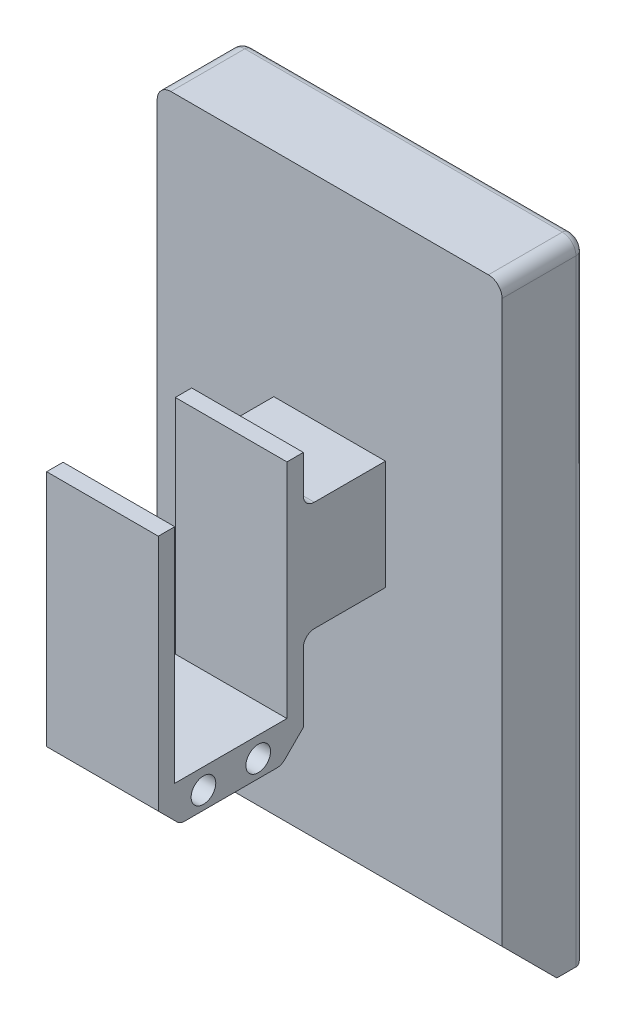
SolidWorks part; units mm, degrees
material "PLA"
ref_plane "Front Plane" through (0, 0, 0) normal (0, 0, 1) x (1, 0, 0)
ref_plane "Top Plane" through (0, 0, 0) normal (0, 1, 0) x (1, 0, 0)
ref_plane "Right Plane" through (0, 0, 0) normal (1, 0, 0) x (0, 0, -1)
sketch "Sketch1" plane through (0, 0, 0) normal (1, 0, 0) x (0, 0, -1)
  line L0 (-10.25, 20.3) -> (10.25, 20.3)
  line L1 (-10.25, -20.3) -> (10.25, -20.3)
  line L2 (-10.25, -20.3) -> (-10.25, 20.3)
  line L4 (10.25, -20.3) -> (10.25, 20.3)
  line L5 (-10.25, -20.3) -> (-13.25, -20.3)
  line L6 (-13.25, -20.3) -> (-13.25, 29.7)
  line L7 (-13.25, 29.7) -> (13.25, 29.7)
  line L8 (10.25, -20.3) -> (13.25, -20.3)
  line L11 (-10.05, 20.1) -> (10.05, 20.1)
  line L13 (13.25, -20.3) -> (13.25, 29.7)
  point P5 (0, 20.3)
  point P6 (-10.25, 0)
  line B0 (-8.8772, 20.1) -> (-10.8742, 20.1) construction
  line B1 (7.4, 20.1) -> (11.2713, 20.1) construction
  line B2 (10.05, 18.0597) -> (10.05, 22.3295) construction
  line B3 (-3.2, -20.1) -> (-12.1258, -20.1) construction
  line B4 (-10.05, -15.1145) -> (-10.05, -21.3251) construction
  line B5 (-10.05, -20.1) -> (10.05, -20.1)
  line B6 (-10.05, -20.1) -> (-10.05, 20.1)
  line B7 (10.05, -20.1) -> (10.05, 20.1)
  circle B8 centre (-5, 24) radius 2.25
  circle B9 centre (5, 24) radius 2.25
  dimension "D1" = 0.2
  dimension "D2" = 0.2
  dimension "D3" = 0.2
  dimension "D4" = 0.2
  dimension "D5" = 3
  dimension "D6" = 50
  dimension "D7" = 3
sketch_block_instance "Block1-1"
sketch_block "Block1"
extrude "Boss-Extrude1" add sketch "Sketch1" along normal blind 20 contours L8 L13 L7 L6 L5 L2 L0 L4 B9 B8
sketch "Sketch2" plane through (0, 0, 0) normal (-1, 0, 0) x (0, 0, 1)
  circle A0 centre (-5, 24) radius 2.25
  circle A1 centre (5, 24) radius 2.25
extrude "Boss-Extrude2" add sketch "Sketch2" against normal blind 10
sketch "Sketch4" plane through (20, 0, 0) normal (1, 0, 0) x (0, 0, -1)
  line L0 (13.25, -20.3) -> (13.25, 29.7) construction
  line L1 (-13.25, 29.7) -> (13.25, 29.7)
  line L2 (-13.25, 29.7) -> (-13.25, 27.2)
  line L3 (-13.25, 27.2) -> (13.25, 27.2)
  line L4 (13.25, 29.7) -> (13.25, 27.2)
  dimension "D1" = 2.5
extrude "Cut-Extrude1" cut sketch "Sketch4" against normal through all
chamfer "Chamfer2" distance 4 angle 45 1 edges at (10, 27.2, -13.25)
chamfer "Chamfer3" distance 4 angle 45 1 edges at (10, 27.2, 13.25)
fillet "Fillet4" radius 2 2 edges at (10, 27.2, -9.25) (10, 27.2, 9.25)
sketch "Sketch7" plane through (20, 0, 0) normal (1, 0, 0) x (0, 0, -1)
  line L0 (13.25, -20.3) -> (13.25, 23.2) construction
  line L3 (28.25, -8.5768) -> (13.25, -8.5768)
  line L6 (13.25, 11.4232) -> (28.25, 11.4232)
  line L8 (28.25, 11.4232) -> (28.25, -8.5768)
  line L9 (13.25, 11.4232) -> (13.25, -8.5768)
  dimension "D1" = 20
  dimension "D2" = 15
extrude "Boss-Extrude5" add sketch "Sketch7" against normal up to surface (20 mm away) up to face at (0, 9.4758, 0)
fillet "Fillet6" radius 2 2 edges at (10, 11.4232, -13.25) (10, -8.5768, -13.25)
ref_plane "Plane2" through (20, 20.3, 10.25) normal (0, 0, -1) x (-1, 0, 0)
sketch "Sketch12" plane through (20, 0, 0) normal (1, 0, 0) x (0, 0, -1)
  line L0 (13.25, 23.2) -> (9.8358, 26.6142) construction
  line L1 (-8.4216, 27.2) -> (8.4216, 27.2) construction
  line L2 (-9.8358, 26.6142) -> (-13.25, 23.2) construction
  line L3 (13.25, 23.2) -> (9.8358, 26.6142)
  line L4 (-8.4216, 27.2) -> (8.4216, 27.2)
  line L5 (-9.8358, 26.6142) -> (-13.25, 23.2)
  line L6 (0, 20.3) -> (-13.25, 20.3) construction
  line L7 (-10.25, 20.3) -> (10.25, 20.3) construction
  line L8 (-13.25, -20.3) -> (-13.25, 23.2) construction
  line L9 (-13.25, 20.3) -> (13.25, 20.3)
  line L10 (13.25, 13.4232) -> (13.25, 23.2) construction
  line L11 (13.25, 20.3) -> (13.25, 23.2)
  line L12 (-13.25, 20.3) -> (-13.25, 23.2)
  arc A0 (9.8358, 26.6142) -> (8.4216, 27.2) centre (8.4216, 25.2) ccw construction
  arc A1 (-8.4216, 27.2) -> (-9.8358, 26.6142) centre (-8.4216, 25.2) ccw construction
  arc A2 (9.8358, 26.6142) -> (8.4216, 27.2) centre (8.4216, 25.2) ccw
  arc A3 (-8.4216, 27.2) -> (-9.8358, 26.6142) centre (-8.4216, 25.2) ccw
sketch "Sketch13" plane through (20, 0, 0) normal (1, 0, 0) x (0, 0, -1)
  line B0 (-13.25, -23.2) -> (-9.8358, -26.6142)
  line B1 (8.4216, -27.2) -> (-8.4216, -27.2)
  line B2 (9.8358, -26.6142) -> (13.25, -23.2)
  line B3 (0, -20.3) -> (13.25, -20.3) construction
  line B4 (13.25, -20.3) -> (-13.25, -20.3)
  line B5 (-13.25, -20.3) -> (-13.25, -23.2)
  line B6 (13.25, -20.3) -> (13.25, -23.2)
  arc B7 (-9.8358, -26.6142) -> (-8.4216, -27.2) centre (-8.4216, -25.2) ccw
  arc B8 (8.4216, -27.2) -> (9.8358, -26.6142) centre (8.4216, -25.2) ccw
  circle B9 centre (5, -24) radius 2.25
  circle B10 centre (-5, -24) radius 2.25
sketch_block_instance "Block2-1"
sketch_block "Block2"
extrude "Boss-Extrude8" add sketch "Sketch13" against normal up to surface (20 mm away) up to face at (0, 6.7916, -6.2595)
extrude "Cut-Extrude2" cut sketch "Sketch12" against normal through all
sketch "Sketch14" plane through (0, 0, 0) normal (-1, 0, 0) x (0, 0, 1)
  circle A0 centre (-5, -24) radius 2.25
  circle A1 centre (5, -24) radius 2.25
extrude "Boss-Extrude9" add sketch "Sketch14" against normal blind 10
sketch "Sketch15" plane through (20, 0, 0) normal (1, 0, 0) x (0, 0, -1)
  line L14 (-10.25, 20.3) -> (-13.25, 20.3)
  line L15 (-13.25, 20.3) -> (-13.25, -23.2)
  line L16 (-13.25, -23.2) -> (-9.8358, -26.6142)
  line L17 (-8.4216, -27.2) -> (8.4216, -27.2)
  line L18 (9.8358, -26.6142) -> (13.25, -23.2)
  line L19 (13.25, -23.2) -> (13.25, -10.5768)
  line L20 (15.25, -8.5768) -> (28.25, -8.5768)
  line L21 (28.25, -8.5768) -> (28.25, 11.4232)
  line L22 (28.25, 11.4232) -> (15.25, 11.4232)
  line L23 (13.25, 13.4232) -> (13.25, 20.3)
  line L24 (13.25, 20.3) -> (10.25, 20.3)
  line L25 (10.25, 20.3) -> (10.25, -20.3)
  line L26 (10.25, -20.3) -> (-10.25, -20.3)
  line L27 (-10.25, -20.3) -> (-10.25, 20.3)
  line L28 (-10.25, 20.3) -> (-13.25, 20.3)
  line L29 (-13.25, 20.3) -> (-13.25, -23.2)
  line L30 (-13.25, -23.2) -> (-9.8358, -26.6142)
  line L31 (-8.4216, -27.2) -> (8.4216, -27.2)
  line L32 (9.8358, -26.6142) -> (13.25, -23.2)
  line L33 (13.25, -23.2) -> (13.25, -10.5768)
  line L34 (15.25, -8.5768) -> (28.25, -8.5768)
  line L36 (28.25, 11.4232) -> (15.25, 11.4232)
  line L37 (13.25, 13.4232) -> (13.25, 20.3)
  line L38 (13.25, 20.3) -> (10.25, 20.3)
  line L39 (10.25, 20.3) -> (10.25, -20.3)
  line L40 (10.25, -20.3) -> (-10.25, -20.3)
  line L41 (-10.25, -20.3) -> (-10.25, 20.3)
  line L42 (28.25, -8.5768) -> (28.25, 11.4232)
  circle A0 centre (5, -24) radius 2.25 construction
  circle A1 centre (-5, -24) radius 2.25 construction
  circle A2 centre (5, -24) radius 2.25
  circle A3 centre (-5, -24) radius 2.25
  arc A6 (-9.8358, -26.6142) -> (-8.4216, -27.2) centre (-8.4216, -25.2) ccw
  arc A7 (8.4216, -27.2) -> (9.8358, -26.6142) centre (8.4216, -25.2) ccw
  arc A8 (15.25, -8.5768) -> (13.25, -10.5768) centre (15.25, -10.5768) ccw
  arc A11 (13.25, 13.4232) -> (15.25, 11.4232) centre (15.25, 13.4232) ccw
  arc A12 (-9.8358, -26.6142) -> (-8.4216, -27.2) centre (-8.4216, -25.2) ccw
  arc A13 (8.4216, -27.2) -> (9.8358, -26.6142) centre (8.4216, -25.2) ccw
  arc A14 (15.25, -8.5768) -> (13.25, -10.5768) centre (15.25, -10.5768) ccw
  arc A17 (13.25, 13.4232) -> (15.25, 11.4232) centre (15.25, 13.4232) ccw
  dimension "D1" = 0
extrude "Boss-Extrude10" add sketch "Sketch15" along normal blind 0.4
sketch "Sketch16" plane through (0, 0, -28.25) normal (0, 0, -1) x (-1, 0, 0)
  line L1 (-41.7, -64.7) -> (21.3, -64.7)
  line L2 (-41.7, -64.7) -> (-41.7, 50.3)
  line L3 (-41.7, 50.3) -> (21.3, 50.3)
  line L4 (21.3, -64.7) -> (21.3, 50.3)
  line L7 (0, 20.3) -> (-20.4, 20.3) construction
  point P6 (-10.2, 20.3)
  point P7 (-10.2, 50.3)
  dimension "D1" = 63
  dimension "D2" = 30
  dimension "D3" = 115
extrude "Boss-Extrude11" add sketch "Sketch16" along normal blind 15
chamfer "Chamfer4" distance 10 angle 45 1 edges at (10.2, -64.7, -28.25)
fillet "Fillet7" radius 2.5 2 edges at (-21.3, 50.3, -35.75) (41.7, 50.3, -35.75)
fillet "Fillet8" radius 1.5 6 edges at (-21.3, -8.45, -43.25) (-20.5678, 49.5678, -43.25) (10.2, 50.3, -43.25) (40.9678, 49.5678, -43.25) (10.2, -64.7, -43.25) (41.7, -8.45, -43.25)
